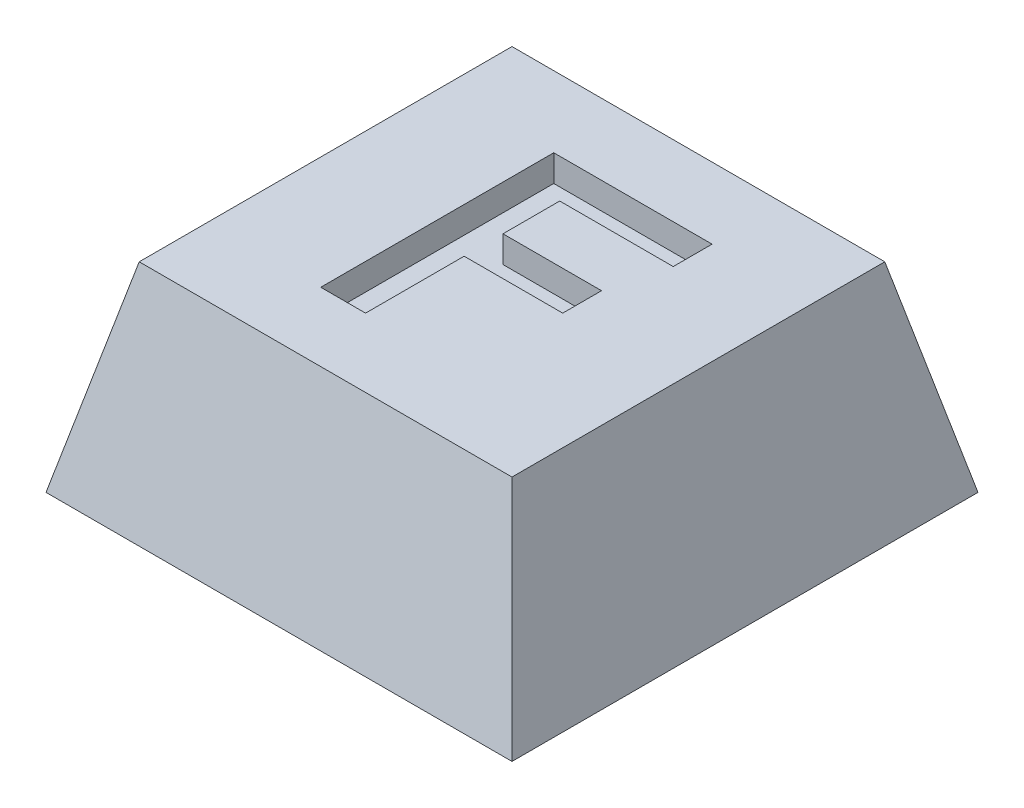
SolidWorks part; units mm, degrees
ref_plane "Front Plane" through (0, 0, 0) normal (0, 0, 1) x (1, 0, 0)
ref_plane "Top Plane" through (0, 0, 0) normal (0, 1, 0) x (1, 0, 0)
ref_plane "Right Plane" through (0, 0, 0) normal (1, 0, 0) x (0, 0, -1)
sketch "Sketch1" plane through (0, 0, 0) normal (0, 1, 0) x (1, 0, 0)
  line L1 (0, 0) -> (7, 0)
  line L2 (0, 0) -> (0, 7)
  line L3 (0, 7) -> (7, 7)
  line L4 (7, 0) -> (7, 7)
  dimension "D1" = 7
  dimension "D2" = 7
extrude "Boss-Extrude1" add sketch "Sketch1" along normal blind 3
sketch "Sketch2" plane through (0, 0, 0) normal (0, 0, 1) x (1, 0, 0)
  line L0 (0, 0) -> (0.7, 3)
  line L1 (0, 3) -> (7, 3) construction
  line L2 (0.7, 3) -> (0, 3)
  line L3 (0, 3) -> (0, 0)
  line L4 (7, 0) -> (6.3, 3)
  line L5 (6.3, 3) -> (7, 3)
  line L6 (7, 3) -> (7, 0)
  dimension "D1" = 0.7
  dimension "D2" = 0.7
extrude "Cut-Extrude1" cut sketch "Sketch2" against normal blind 7
sketch "Sketch3" plane through (0, 0, 0) normal (1, 0, 0) x (0, 0, -1)
  line L0 (0, 0) -> (0.7, 3)
  line L1 (7, 3) -> (0, 3) construction
  line L2 (0.7, 3) -> (0, 3)
  line L3 (0, 3) -> (0, 0)
  line L4 (7, 3) -> (6.3, 3)
  line L5 (6.3, 3) -> (7, 0)
  line L6 (7, 3) -> (7, 0)
  dimension "D1" = 0.7
  dimension "D2" = 0.7
extrude "Cut-Extrude2" cut sketch "Sketch3" along normal blind 11
sketch "Sketch4" plane through (0, 0, 0) normal (0, -1, 0) x (1, 0, 0)
  line L0 (3.5, 0) -> (3.5, -7) construction
  line L1 (0, 0) -> (7, 0) construction
  line L2 (7, -7) -> (0, -7) construction
  line L3 (0, -3.5) -> (7, -3.5) construction
  line L4 (0, -7) -> (0, 0) construction
  line L5 (7, 0) -> (7, -7) construction
  circle A0 centre (3.5, -3.5) radius 1.8
  dimension "D1" = 3.6
extrude "Cut-Extrude3" cut sketch "Sketch4" against normal blind 0.8
sketch "Sketch5" plane through (0, 3, 0) normal (0, 1, 0) x (1, 0, 0)
  text T0 "F" font "Arial" height 3.5
extrude "Cut-Extrude4" cut sketch "Sketch5" against normal blind 0.4
